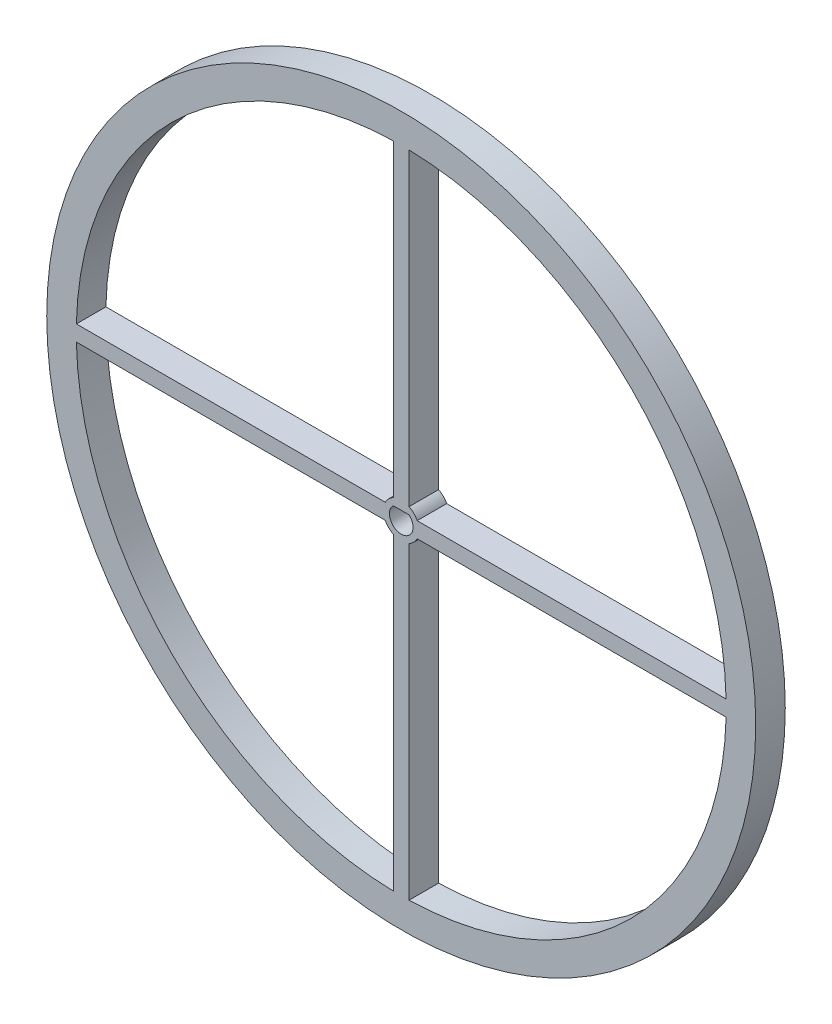
SolidWorks part; units mm, degrees
ref_plane "Front" through (0, 0, 0) normal (0, 0, 1) x (1, 0, 0)
ref_plane "Top" through (0, 0, 0) normal (0, 1, 0) x (1, 0, 0)
ref_plane "Right" through (0, 0, 0) normal (1, 0, 0) x (0, 0, -1)
sketch "Sketch1" plane through (0, 0, 0) normal (0, 0, 1) x (1, 0, 0)
  line L0 (1.325, 1.4981) -> (-1.325, 1.4981)
  line L1 (-1.325, 2.6915) -> (-1.325, 54.984)
  line L3 (-1.325, -54.984) -> (-1.325, -2.6915)
  line L5 (1.325, -54.984) -> (1.325, -2.6915)
  line L6 (-1.325, -54.984) -> (-0.0723, -2.9991) construction
  line L7 (-1.3514, 56.0782) -> (-0.0723, 2.9991) construction
  line L8 (-54.984, -1.325) -> (-2.6915, -1.325)
  line L10 (-54.984, 1.325) -> (-2.6915, 1.325)
  line L12 (-54.984, -1.325) -> (-2.9991, -0.0723) construction
  line L13 (-54.984, 1.325) -> (-2.9991, 0.0723) construction
  line L15 (0.0723, 2.9991) -> (1.325, 54.984) construction
  line L16 (1.325, 2.6915) -> (1.325, 54.984)
  line L18 (2.9991, -0.0723) -> (54.984, -1.325) construction
  line L20 (2.6915, -1.325) -> (54.984, -1.325)
  line L21 (0.0723, -2.9991) -> (1.325, -54.984) construction
  line L23 (2.6915, 1.325) -> (54.984, 1.325)
  line L24 (2.9991, 0.0723) -> (54.984, 1.325) construction
  circle A0 centre (0, 0) radius 60
  arc A1 (-54.984, -1.325) -> (-1.325, -54.984) centre (0, 0) ccw
  circle A2 centre (0, 0) radius 3
  arc A3 (-1.325, 1.4981) -> (1.325, 1.4981) centre (0, 0) ccw
  arc A4 (-1.325, 54.984) -> (-54.984, 1.325) centre (0, 0) ccw
  arc A5 (54.984, 1.325) -> (1.325, 54.984) centre (0, 0) ccw
  arc A6 (1.325, -54.984) -> (54.984, -1.325) centre (0, 0) ccw
  dimension "D1" = 120
  dimension "D2" = 110
  dimension "D3" = 6
  dimension "D4" = 4
  dimension "D5" = 2.65
  dimension "D6" = 2.65
  dimension "D7" = 2.65
extrude "Boss-Extrude2" add sketch "Sketch1" along normal blind 5 contours A0 A6 L5 A2 L3 A1 L8 L10 A4 L1 L16 A5 L23 L20 | A2 A3 L0
